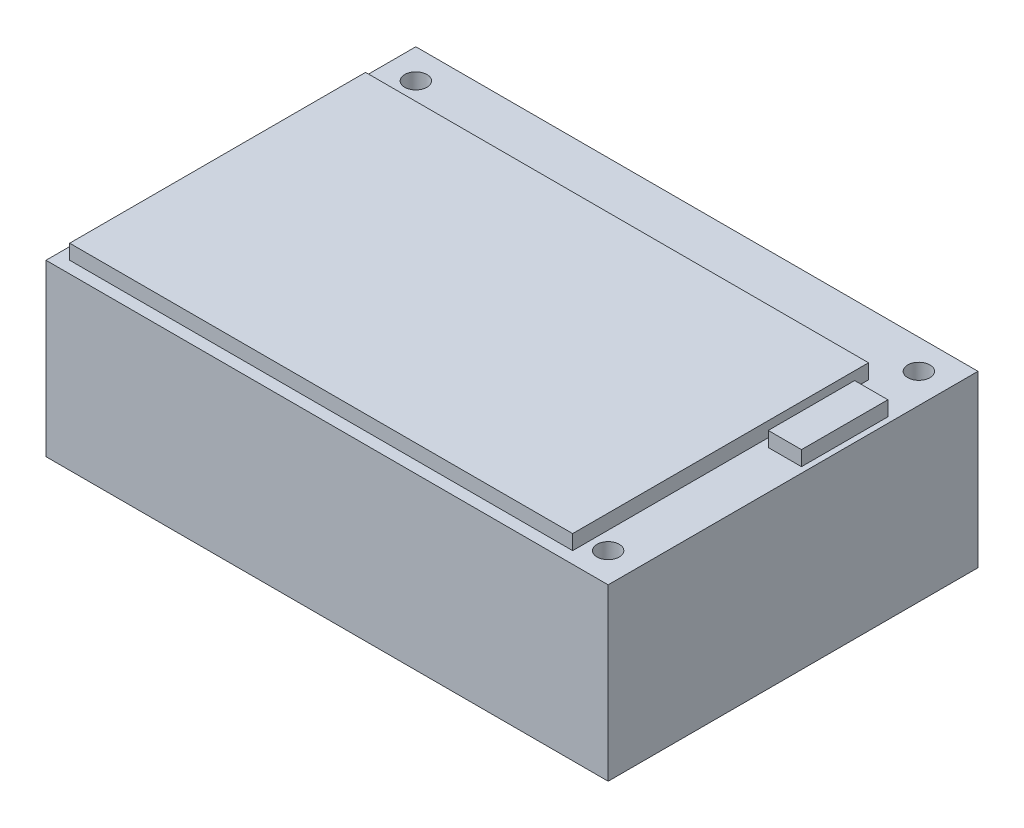
SolidWorks part; units mm, degrees
ref_plane "Front Plane" through (0, 0, 0) normal (0, 0, 1) x (1, 0, 0)
ref_plane "Top Plane" through (0, 0, 0) normal (0, 1, 0) x (1, 0, 0)
ref_plane "Right Plane" through (0, 0, 0) normal (1, 0, 0) x (0, 0, -1)
sketch "Sketch1" plane through (0, 0, 0) normal (0, 1, 0) x (1, 0, 0)
  line L1 (-48.26, 31.75) -> (48.26, 31.75)
  line L2 (-48.26, 31.75) -> (-48.26, -31.75)
  line L3 (-48.26, -31.75) -> (48.26, -31.75)
  line L4 (48.26, 31.75) -> (48.26, -31.75)
  line L5 (-48.26, 31.75) -> (48.26, -31.75) construction
  line L6 (-48.26, -31.75) -> (48.26, 31.75) construction
  line L7 (-43.18, 26.67) -> (43.18, 26.67) construction
  line L8 (-43.18, 26.67) -> (-43.18, -26.67) construction
  line L9 (-43.18, -26.67) -> (43.18, -26.67) construction
  line L10 (43.18, 26.67) -> (43.18, -26.67) construction
  line L11 (-43.18, 26.67) -> (43.18, -26.67) construction
  line L12 (-43.18, -26.67) -> (43.18, 26.67) construction
  circle A0 centre (-43.18, 26.67) radius 1.905
  circle A1 centre (43.18, 26.67) radius 1.905
  circle A2 centre (43.18, -26.67) radius 1.905
  circle A3 centre (-43.18, -26.67) radius 1.905
  point P0 (0, 0)
  point P6 (0, 0)
  dimension "D5" = 3.81
  dimension "D1" = 96.52
  dimension "D2" = 63.5
  dimension "D3" = 86.36
  dimension "D4" = 53.34
extrude "Boss-Extrude1" add sketch "Sketch1" along normal blind 29.21
sketch "Sketch2" plane through (0, 29.21, 0) normal (0, 1, 0) x (1, 0, 0)
  line L0 (-48.26, 31.75) -> (-48.26, -31.75) construction
  line L1 (-46.228, -29.718) -> (40.132, -29.718)
  line L2 (-46.228, -29.718) -> (-46.228, 21.082)
  line L3 (-46.228, 21.082) -> (40.132, 21.082)
  line L4 (40.132, -29.718) -> (40.132, 21.082)
  line L5 (-48.26, -31.75) -> (48.26, -31.75) construction
  line L7 (41.5886, 17.244) -> (47.2943, 17.244)
  line L8 (41.5886, 17.244) -> (41.5886, 2.4091)
  line L9 (41.5886, 2.4091) -> (47.2943, 2.4091)
  line L10 (47.2943, 17.244) -> (47.2943, 2.4091)
  dimension "D1" = 2.032
  dimension ".06" = 2.032
  dimension "D2" = 86.36
  dimension "D3" = 50.8
extrude "Boss-Extrude2" add sketch "Sketch2" along normal blind 2.54
sketch "Sketch3" plane through (0, 0, 0) normal (0, -1, 0) x (1, 0, 0)
  line L0 (-48.26, -31.75) -> (-48.26, 31.75) construction
  line L1 (-48.26, 31.75) -> (48.26, 31.75) construction
  circle A0 centre (-25.4, 12.7) radius 1.27
  dimension "D1" = 2.54
  dimension "D2" = 22.86
  dimension "D3" = 19.05
extrude "Cut-Extrude1" cut sketch "Sketch3" against normal blind 2.54
sketch "Sketch4" plane through (0, 0, -31.75) normal (0, 0, -1) x (-1, 0, 0)
  line L0 (-48.26, 10.287) -> (-31.496, 10.287) construction
  line L1 (-48.26, 29.21) -> (-48.26, 0) construction
  line L2 (-31.496, 10.287) -> (-20.32, 10.287) construction
  line L3 (-20.32, 10.287) -> (-8.382, 10.287) construction
  line L4 (-8.382, 10.287) -> (2.54, 10.287) construction
  line L5 (2.54, 10.287) -> (48.26, 10.287) construction
  line L6 (48.26, 29.21) -> (48.26, 0) construction
  line L8 (-35.306, 13.462) -> (-27.686, 13.462)
  line L9 (-35.306, 13.462) -> (-35.306, 7.112)
  line L10 (-35.306, 7.112) -> (-27.686, 7.112)
  line L11 (-27.686, 13.462) -> (-27.686, 7.112)
  line L12 (-35.306, 13.462) -> (-27.686, 7.112) construction
  line L13 (-35.306, 7.112) -> (-27.686, 13.462) construction
  line L14 (-25.4, 13.462) -> (-15.24, 13.462)
  line L15 (-25.4, 13.462) -> (-25.4, 7.112)
  line L16 (-25.4, 7.112) -> (-15.24, 7.112)
  line L17 (-15.24, 13.462) -> (-15.24, 7.112)
  line L18 (-25.4, 13.462) -> (-15.24, 7.112) construction
  line L19 (-25.4, 7.112) -> (-15.24, 13.462) construction
  line L20 (-12.192, 13.462) -> (-4.572, 13.462)
  line L21 (-12.192, 13.462) -> (-12.192, 7.112)
  line L22 (-12.192, 7.112) -> (-4.572, 7.112)
  line L23 (-4.572, 13.462) -> (-4.572, 7.112)
  line L24 (-12.192, 13.462) -> (-4.572, 7.112) construction
  line L25 (-12.192, 7.112) -> (-4.572, 13.462) construction
  line L26 (-2.54, 13.462) -> (7.62, 13.462)
  line L27 (-2.54, 13.462) -> (-2.54, 7.112)
  line L28 (-2.54, 7.112) -> (7.62, 7.112)
  line L29 (7.62, 13.462) -> (7.62, 7.112)
  line L30 (-2.54, 13.462) -> (7.62, 7.112) construction
  line L31 (-2.54, 7.112) -> (7.62, 13.462) construction
  line L33 (-40.132, 31.75) -> (46.228, 31.75) construction
  dimension "D1" = 18.288
  dimension "D2" = 10.16
  dimension "D3" = 7.62
  dimension "D4" = 16.764
  dimension "D5" = 27.94
  dimension "D6" = 39.878
  dimension "D7" = 50.8
  dimension "D8" = 6.35
extrude "Boss-Extrude3" add sketch "Sketch4" along normal blind 10.16
